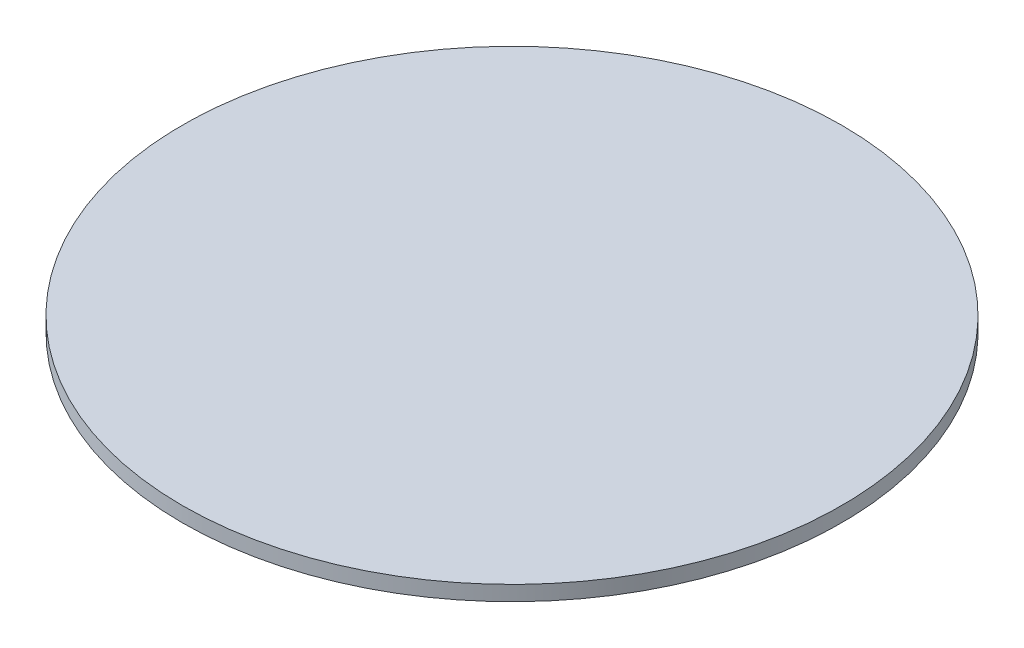
SolidWorks part; units mm, degrees
ref_plane "Спереди" through (0, 0, 0) normal (0, 0, 1) x (1, 0, 0)
ref_plane "Сверху" through (0, 0, 0) normal (0, 1, 0) x (1, 0, 0)
ref_plane "Справа" through (0, 0, 0) normal (1, 0, 0) x (0, 0, -1)
sketch "Sketch1" plane through (0, 0, 0) normal (0, 1, 0) x (1, 0, 0)
  circle A2 centre (0, 0) radius 44
  point P3 (-20.6648, -14.0701)
  point P5 (-44, 0)
extrude "Boss-Extrude1" add sketch "Sketch1" against normal blind 2
sketch "Sketch2" plane through (0, 0, 0) normal (0, 1, 0) x (1, 0, 0)
  circle A0 centre (0, 0) radius 23.8685
